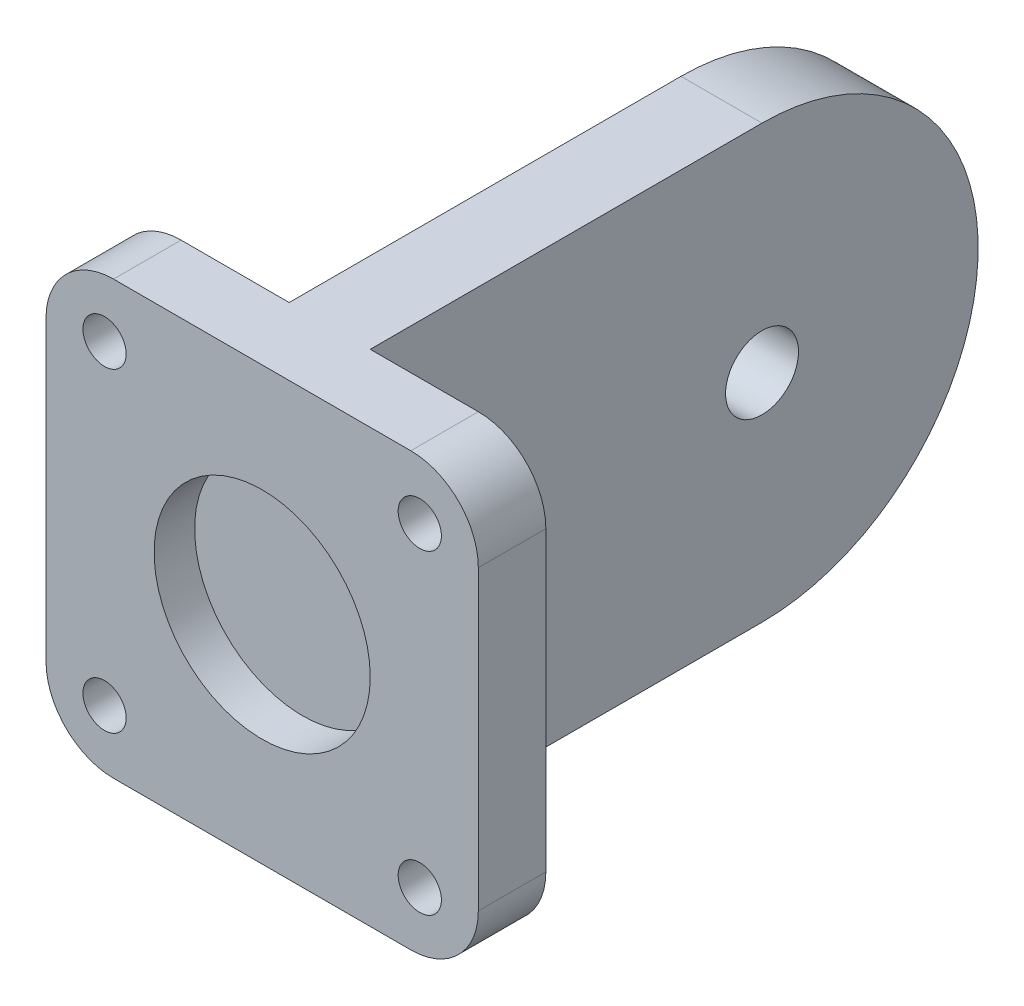
SolidWorks part; units mm, degrees
ref_plane "Front Plane" through (0, 0, 0) normal (0, 0, 1) x (1, 0, 0)
ref_plane "Top Plane" through (0, 0, 0) normal (0, 1, 0) x (1, 0, 0)
ref_plane "Right Plane" through (0, 0, 0) normal (1, 0, 0) x (0, 0, -1)
sketch "Sketch1" plane through (0, 0, 0) normal (0, 0, 1) x (1, 0, 0)
  line L0 (0, -25.4879) -> (11.6673, -13.8206) construction
  line L13 (0, -25.4879) -> (0, -11.4649) construction
  line L14 (-15.2165, -25.4879) -> (15.2165, -25.4879) construction
  line L16 (-11, -9.4879) -> (11, -9.4879)
  line L17 (-16, -14.4879) -> (-16, -36.4879)
  line L18 (-11, -41.4879) -> (11, -41.4879)
  line L19 (16, -14.4879) -> (16, -36.4879)
  circle A1 centre (11.6673, -13.8206) radius 1.6
  arc A17 (11, -9.4879) -> (16, -14.4879) centre (11, -14.4879) cw
  arc A18 (11, -41.4879) -> (16, -36.4879) centre (11, -36.4879) ccw
  arc A19 (-16, -36.4879) -> (-11, -41.4879) centre (-11, -36.4879) ccw
  arc A20 (-11, -9.4879) -> (-16, -14.4879) centre (-11, -14.4879) ccw
  circle A21 centre (11.6673, -37.1551) radius 1.6
  circle A22 centre (-11.6673, -37.1551) radius 1.6
  circle A23 centre (-11.6673, -13.8206) radius 1.6
  point P16 (0, -25.4879)
  point P32 (16, -9.4879)
  point P35 (16, -41.4879)
  point P40 (-16, -9.4879)
  dimension "D1" = 4
  dimension "D7" = 5
  dimension "D3" = 16
  dimension "D4" = 32
  dimension "D5" = 16
  dimension "D6" = 32
  dimension "D8" = 16.5
  dimension "D9" = 45
extrude "Boss-Extrude1" add sketch "Sketch1" against normal blind 5
sketch "Sketch2" plane through (0, -9.4879, 0) normal (0, 1, 0) x (1, 0, 0)
  line L0 (-11, 0) -> (11, 0) construction
  line L1 (3, 0) -> (-3, 0)
  line L2 (3, 0) -> (3, 50)
  line L3 (3, 50) -> (-3, 50)
  line L4 (-3, 0) -> (-3, 50)
  line L5 (0, 2.9184) -> (0, 28.4617) construction
  dimension "D1" = 3
  dimension "D2" = 3
  dimension "D3" = 50
extrude "Boss-Extrude2" add sketch "Sketch2" against normal up to surface (32 mm away) up to face at (0, -41.4879, -2.5)
sketch "Sketch3" plane through (-3, 0, 0) normal (-1, 0, 0) x (0, 0, 1)
  line L0 (-50, -41.4879) -> (-50, -9.4879) construction
  circle A0 centre (-34, -25.4879) radius 2.7
  dimension "D1" = 16
extrude "Cut-Extrude1" cut sketch "Sketch3" against normal blind 7
sketch "Sketch4" plane through (0, 0, 0) normal (0, 0, 1) x (1, 0, 0)
  circle A0 centre (0, -25.4879) radius 8
extrude "Cut-Extrude2" cut sketch "Sketch4" against normal blind 3
ref_plane "Plane1" through (0, -35.4879, 0) normal (0, -1, 0) x (-1, 0, 0)
sketch "Sketch7" plane through (-3, 0, 0) normal (-1, 0, 0) x (0, 0, 1)
  line L0 (-50, -25.4879) -> (-34, -25.4879) construction
  line L1 (-50, -41.4879) -> (-50, -9.4879) construction
  line L3 (-34, -9.4879) -> (-52.3738, -9.4879)
  line L4 (-52.3738, -9.4879) -> (-52.3738, -41.4879)
  line L5 (-52.3738, -41.4879) -> (-34, -41.4879)
  arc A0 (-34, -9.4879) -> (-34, -41.4879) centre (-34, -25.4879) ccw
  dimension "D1" = 16
extrude "Cut-Extrude3" cut sketch "Sketch7" against normal through all
